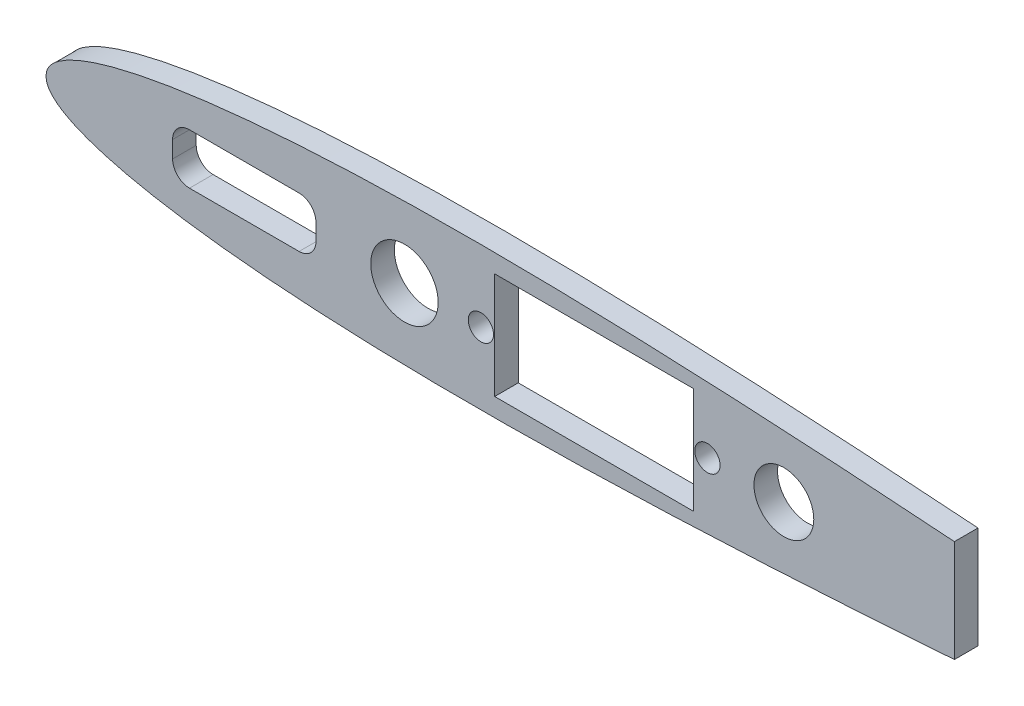
SolidWorks part; units mm, degrees
material "Фанера"
ref_plane "Front Plane" through (0, 0, 0) normal (0, 0, 1) x (1, 0, 0)
ref_plane "Top Plane" through (0, 0, 0) normal (0, 1, 0) x (1, 0, 0)
ref_plane "Right Plane" through (0, 0, 0) normal (1, 0, 0) x (0, 0, -1)
curve "Кривая1"
  spline degree 3 poles (110, 0, 0) (110.0276, -0.2367, 0) (110.0855, -0.7342, 0) (110.5302, -1.4271, 0) (111.1963, -2.0786, 0) (112.1098, -2.7013, 0) (113.2568, -3.2993, 0) (114.6379, -3.8731, 0) (116.2477, -4.4214, 0) (118.0813, -4.9426, 0) (120.1331, -5.4348, 0) (122.3972, -5.8961, 0) (124.8672, -6.3247, 0) (127.537, -6.7187, 0) (130.3997, -7.0764, 0) (133.4488, -7.3965, 0) (136.6771, -7.6776, 0) (140.0777, -7.9187, 0) (143.6433, -8.119, 0) (147.3662, -8.278, 0) (151.2389, -8.3955, 0) (155.2534, -8.4715, 0) (159.4016, -8.5065, 0) (163.6751, -8.501, 0) (168.0653, -8.456, 0) (172.5632, -8.3725, 0) (177.1595, -8.252, 0) (181.8446, -8.096, 0) (186.6087, -7.9062, 0) (191.4413, -7.6846, 0) (196.3316, -7.4331, 0) (201.2684, -7.1538, 0) (206.2396, -6.8489, 0) (211.233, -6.5205, 0) (216.2352, -6.1709, 0) (221.2323, -5.8022, 0) (226.2093, -5.417, 0) (231.1504, -5.0174, 0) (236.0382, -4.6058, 0) (240.8542, -4.1849, 0) (245.5777, -3.7574, 0) (250.1862, -3.3262, 0) (254.6542, -2.8948, 0) (258.9526, -2.4672, 0) (263.0477, -2.0479, 0) (266.899, -1.6426, 0) (270.4558, -1.2586, 0) (273.6512, -0.9053, 0) (276.3854, -0.5964, 0) (278.4526, -0.359, 0) (279.592, -0.2261, 0) (280, -0.1785, 0) knots 0 0 0 0 0.004099 0.008615 0.013935 0.020278 0.027753 0.03641 0.046266 0.05732 0.069559 0.082963 0.097507 0.113164 0.129903 0.14769 0.166492 0.186272 0.206992 0.228612 0.251092 0.274389 0.298458 0.323254 0.348728 0.37483 0.401509 0.42871 0.456376 0.484448 0.512864 0.541558 0.570462 0.599504 0.628607 0.65769 0.686667 0.715445 0.743924 0.771995 0.79954 0.826428 0.852512 0.877624 0.901571 0.924121 0.944989 0.963804 0.980044 0.992855 1 1 1 1
curve "Кривая2"
  spline degree 3 poles (280, 0.1785, 0) (279.592, 0.2261, 0) (278.4526, 0.359, 0) (276.3854, 0.5964, 0) (273.6512, 0.9053, 0) (270.4558, 1.2586, 0) (266.899, 1.6426, 0) (263.0477, 2.0479, 0) (258.9526, 2.4672, 0) (254.6542, 2.8948, 0) (250.1862, 3.3262, 0) (245.5777, 3.7574, 0) (240.8542, 4.1849, 0) (236.0382, 4.6058, 0) (231.1504, 5.0174, 0) (226.2093, 5.417, 0) (221.2323, 5.8022, 0) (216.2352, 6.1709, 0) (211.233, 6.5205, 0) (206.2396, 6.8489, 0) (201.2684, 7.1538, 0) (196.3316, 7.4331, 0) (191.4413, 7.6846, 0) (186.6087, 7.9062, 0) (181.8446, 8.096, 0) (177.1595, 8.252, 0) (172.5632, 8.3725, 0) (168.0653, 8.456, 0) (163.6751, 8.501, 0) (159.4016, 8.5065, 0) (155.2534, 8.4715, 0) (151.2389, 8.3955, 0) (147.3662, 8.278, 0) (143.6433, 8.119, 0) (140.0777, 7.9187, 0) (136.6771, 7.6776, 0) (133.4488, 7.3965, 0) (130.3997, 7.0764, 0) (127.537, 6.7187, 0) (124.8672, 6.3247, 0) (122.3972, 5.8961, 0) (120.1331, 5.4348, 0) (118.0813, 4.9426, 0) (116.2477, 4.4214, 0) (114.6379, 3.8731, 0) (113.2568, 3.2993, 0) (112.1098, 2.7013, 0) (111.1963, 2.0786, 0) (110.5302, 1.4271, 0) (110.0855, 0.7342, 0) (110.0276, 0.2367, 0) (110, 0, 0) knots 0 0 0 0 0.007145 0.019956 0.036196 0.055011 0.075879 0.098429 0.122376 0.147488 0.173572 0.20046 0.228005 0.256076 0.284555 0.313333 0.34231 0.371393 0.400496 0.429538 0.458442 0.487136 0.515552 0.543624 0.57129 0.598491 0.62517 0.651272 0.676746 0.701542 0.725611 0.748908 0.771388 0.793008 0.813728 0.833508 0.85231 0.870097 0.886836 0.902493 0.917037 0.930441 0.94268 0.953734 0.96359 0.972247 0.979722 0.986065 0.991385 0.995901 1 1 1 1
sketch "Эскиз1" plane through (0, 0, 0) normal (0, 0, 1) x (1, 0, 0)
  line L0 (105.1708, 0) -> (280.7263, 0) construction
  line L1 (280.0739, 0) -> (280.0739, 24.3846) construction
  line L2 (110, -5.3315) -> (110, 17.5304) construction
  line L3 (152.5185, 18.8331) -> (152.5185, -21.3473) construction
  line L4 (223.3826, 13.2402) -> (223.3826, -18.4275) construction
  line L5 (217.7476, 6.0581) -> (217.7476, -6.0581)
  line L6 (127.0185, -3) -> (140.0185, -3)
  line L7 (125.0185, -1) -> (125.0185, 1)
  line L8 (127.0185, 3) -> (140.0185, 3)
  line L9 (142.0185, -1) -> (142.0185, 1)
  line L10 (125.0185, -3) -> (142.0185, 3) construction
  line L11 (125.0185, 3) -> (142.0185, -3) construction
  line L16 (175.0185, 15.5451) -> (175.0185, -13.0112) construction
  line L17 (163.2185, -6.3) -> (186.8185, -6.3)
  line L18 (163.2185, -6.3) -> (163.2185, 6.3)
  line L19 (163.2185, 6.3) -> (186.8185, 6.3)
  line L20 (186.8185, -6.3) -> (186.8185, 6.3)
  line L21 (163.2185, -6.3) -> (186.8185, 6.3) construction
  line L22 (163.2185, 6.3) -> (186.8185, -6.3) construction
  line L23 (186.8185, 6.3) -> (190.0885, 6.3) construction
  line L24 (190.0885, 6.3) -> (190.0885, -6.3) construction
  line L25 (190.0885, -6.3) -> (186.8185, -6.3) construction
  arc A0 (280, 0.1785) -> (280, -0.1785) centre (279.8215, 0) cw
  circle A1 centre (152.5185, 0) radius 4
  circle A2 centre (197.5185, 0) radius 3.55
  arc A7 (125.0185, 1) -> (127.0185, 3) centre (127.0185, 1) cw
  arc A8 (127.0185, -3) -> (125.0185, -1) centre (127.0185, -1) cw
  arc A9 (140.0185, -3) -> (142.0185, -1) centre (140.0185, -1) ccw
  arc A10 (140.0185, 3) -> (142.0185, 1) centre (140.0185, 1) cw
  arc A11 (223.3826, 5.635) -> (223.3826, -5.635) centre (223.3826, 0) ccw
  circle A12 centre (223.3826, 0) radius 1
  circle A13 centre (188.4535, 0) radius 1.5
  circle A14 centre (161.5835, 0) radius 1.5
  spline S0 degree 3 poles (-1802.3351, -584.8827) (164.5267, 33.7772) (105.6543, 6.1699) (110.5302, -1.4271) (111.1963, -2.0786) (112.1098, -2.7013) (113.2568, -3.2993) (114.6379, -3.8731) (116.2477, -4.4214) (118.0813, -4.9426) (120.1331, -5.4348) (122.3972, -5.8961) (124.8672, -6.3247) (127.537, -6.7187) (130.3997, -7.0764) (133.4488, -7.3965) (136.6771, -7.6776) (140.0777, -7.9187) (143.6433, -8.119) (147.3662, -8.278) (151.2389, -8.3955) (155.2534, -8.4715) (159.4016, -8.5065) (163.6751, -8.501) (168.0653, -8.456) (172.5632, -8.3725) (177.1595, -8.252) (181.8446, -8.096) (186.6087, -7.9062) (191.4413, -7.6846) (196.3316, -7.4331) (201.2684, -7.1538) (206.2396, -6.8489) (211.233, -6.5205) (216.2352, -6.1709) (221.2323, -5.8022) (226.2093, -5.417) (231.1504, -5.0174) (236.0382, -4.6058) (240.8542, -4.1849) (247.0711, -3.6222) (253.1161, -3.0479) (258.9526, -2.4672) (263.0477, -2.0479) (266.899, -1.6426) (270.4558, -1.2586) (273.6512, -0.9053) (276.3854, -0.5964) (359.5279, 8.955) (440.5611, 28.5776) (751.5392, -1938.3855) knots -0.13886 -0.13886 -0.13886 -0.13886 0.004099 0.008615 0.013935 0.020278 0.027753 0.03641 0.046266 0.05732 0.069559 0.082963 0.097507 0.113164 0.129903 0.14769 0.166492 0.186272 0.206992 0.228612 0.251092 0.274389 0.298458 0.323254 0.348728 0.37483 0.401509 0.42871 0.456376 0.484448 0.512864 0.541558 0.570462 0.599504 0.628607 0.65769 0.686667 0.715445 0.743924 0.771995 0.79954 0.852512 0.877624 0.901571 0.924121 0.944989 0.963804 0.980044 0.992855 2.419626 2.419626 2.419626 2.419626 only from (110, 0) to (280, -0.1785) construction
  spline S1 degree 3 poles (751.5383, 1938.3796) (440.561, -28.5775) (359.5279, -8.955) (276.3854, 0.5964) (273.6512, 0.9053) (270.4558, 1.2586) (266.899, 1.6426) (263.0477, 2.0479) (258.9526, 2.4672) (253.1161, 3.0479) (247.0711, 3.6222) (240.8542, 4.1849) (236.0382, 4.6058) (231.1504, 5.0174) (226.2093, 5.417) (221.2323, 5.8022) (216.2352, 6.1709) (211.233, 6.5205) (206.2396, 6.8489) (201.2684, 7.1538) (196.3316, 7.4331) (191.4413, 7.6846) (186.6087, 7.9062) (181.8446, 8.096) (177.1595, 8.252) (172.5632, 8.3725) (168.0653, 8.456) (163.6751, 8.501) (159.4016, 8.5065) (155.2534, 8.4715) (151.2389, 8.3955) (147.3662, 8.278) (143.6433, 8.119) (140.0777, 7.9187) (136.6771, 7.6776) (133.4488, 7.3965) (130.3997, 7.0764) (127.537, 6.7187) (124.8672, 6.3247) (122.3972, 5.8961) (120.1331, 5.4348) (118.0813, 4.9426) (116.2477, 4.4214) (114.6379, 3.8731) (113.2568, 3.2993) (112.1098, 2.7013) (111.1963, 2.0786) (110.5302, 1.4271) (105.6546, -6.1694) (164.5198, -33.7739) (-1801.974, 584.7691) knots -1.419625 -1.419625 -1.419625 -1.419625 0.007145 0.019956 0.036196 0.055011 0.075879 0.098429 0.122376 0.147488 0.20046 0.228005 0.256076 0.284555 0.313333 0.34231 0.371393 0.400496 0.429538 0.458442 0.487136 0.515552 0.543624 0.57129 0.598491 0.62517 0.651272 0.676746 0.701542 0.725611 0.748908 0.771388 0.793008 0.813728 0.833508 0.85231 0.870097 0.886836 0.902493 0.917037 0.930441 0.94268 0.953734 0.96359 0.972247 0.979722 0.986065 0.991385 0.995901 1.138851 1.138851 1.138851 1.138851 only from (280, 0.1785) to (110, 0) construction
  spline S2 degree 3 poles (110, 0) (110.0276, -0.2367) (110.0855, -0.7342) (110.5302, -1.4271) (111.1963, -2.0786) (112.1098, -2.7013) (113.2568, -3.2993) (114.6379, -3.8731) (116.2477, -4.4214) (118.0813, -4.9426) (120.1331, -5.4348) (122.3972, -5.8961) (124.8672, -6.3247) (127.537, -6.7187) (130.3997, -7.0764) (133.4488, -7.3965) (136.6771, -7.6776) (140.0777, -7.9187) (143.6433, -8.119) (147.3662, -8.278) (151.2389, -8.3955) (155.2534, -8.4715) (159.4016, -8.5065) (163.6751, -8.501) (168.0653, -8.456) (172.5632, -8.3725) (177.1595, -8.252) (181.8446, -8.096) (186.6087, -7.9062) (191.4413, -7.6846) (196.3316, -7.4331) (201.2684, -7.1538) (206.2396, -6.8489) (211.233, -6.5205) (216.2352, -6.1709) (221.2323, -5.8022) (226.2093, -5.417) (231.1504, -5.0174) (236.0382, -4.6058) (240.8542, -4.1849) (247.0711, -3.6222) (253.1161, -3.0479) (258.9526, -2.4672) (263.0477, -2.0479) (266.899, -1.6426) (270.4558, -1.2586) (273.6512, -0.9053) (276.3854, -0.5964) (278.4526, -0.359) (279.592, -0.2261) (280, -0.1785) knots 0 0 0 0 0.004099 0.008615 0.013935 0.020278 0.027753 0.03641 0.046266 0.05732 0.069559 0.082963 0.097507 0.113164 0.129903 0.14769 0.166492 0.186272 0.206992 0.228612 0.251092 0.274389 0.298458 0.323254 0.348728 0.37483 0.401509 0.42871 0.456376 0.484448 0.512864 0.541558 0.570462 0.599504 0.628607 0.65769 0.686667 0.715445 0.743924 0.771995 0.79954 0.852512 0.877624 0.901571 0.924121 0.944989 0.963804 0.980044 0.992855 1 1 1 1
  spline S3 degree 3 poles (280, 0.1785) (279.592, 0.2261) (278.4526, 0.359) (276.3854, 0.5964) (273.6512, 0.9053) (270.4558, 1.2586) (266.899, 1.6426) (263.0477, 2.0479) (258.9526, 2.4672) (253.1161, 3.0479) (247.0711, 3.6222) (240.8542, 4.1849) (236.0382, 4.6058) (231.1504, 5.0174) (226.2093, 5.417) (221.2323, 5.8022) (216.2352, 6.1709) (211.233, 6.5205) (206.2396, 6.8489) (201.2684, 7.1538) (196.3316, 7.4331) (191.4413, 7.6846) (186.6087, 7.9062) (181.8446, 8.096) (177.1595, 8.252) (172.5632, 8.3725) (168.0653, 8.456) (163.6751, 8.501) (159.4016, 8.5065) (155.2534, 8.4715) (151.2389, 8.3955) (147.3662, 8.278) (143.6433, 8.119) (140.0777, 7.9187) (136.6771, 7.6776) (133.4488, 7.3965) (130.3997, 7.0764) (127.537, 6.7187) (124.8672, 6.3247) (122.3972, 5.8961) (120.1331, 5.4348) (118.0813, 4.9426) (116.2477, 4.4214) (114.6379, 3.8731) (113.2568, 3.2993) (112.1098, 2.7013) (111.1963, 2.0786) (110.5302, 1.4271) (110.0855, 0.7342) (110.0276, 0.2367) (110, 0) knots 0 0 0 0 0.007145 0.019956 0.036196 0.055011 0.075879 0.098429 0.122376 0.147488 0.20046 0.228005 0.256076 0.284555 0.313333 0.34231 0.371393 0.400496 0.429538 0.458442 0.487136 0.515552 0.543624 0.57129 0.598491 0.62517 0.651272 0.676746 0.701542 0.725611 0.748908 0.771388 0.793008 0.813728 0.833508 0.85231 0.870097 0.886836 0.902493 0.917037 0.930441 0.94268 0.953734 0.96359 0.972247 0.979722 0.986065 0.991385 0.995901 1 1 1 1
  point P19 (175.0185, 0)
  point P22 (133.5185, 0)
  point P31 (223.3826, -5.635)
  point P37 (188.4535, 6.3)
  point P54 (223.3826, 5.635)
  point P55 (223.3826, -5.635)
  point P56 (223.3826, 5.635)
  dimension "D1" = 0.2524
  dimension "D3" = 8
  dimension "D14" = 5.635
  dimension "D15" = 2
  dimension "D10" = 2
  dimension "D16" = 3
  dimension "D18" = 7.1
  dimension "D2" = 170.0739
  dimension "D4" = 42.5185
  dimension "D5" = 56.6913
  dimension "D6" = 45
  dimension "D7" = 6
  dimension "D8" = 17
  dimension "D9" = 19
  dimension "D11" = 12.6
  dimension "D12" = 23.6
  dimension "D13" = 22.5
  dimension "D17" = 3.27
extrude "Бобышка-Вытянуть1" add sketch "Эскиз1" along normal mid plane 2.8
equation "\"D4@Эскиз1\"=\"D2@Эскиз1\"/4"
equation "\"D5@Эскиз1\"=\"D2@Эскиз1\"/3"
equation "\"D13@Эскиз1\"=\"D6@Эскиз1\"/2"
